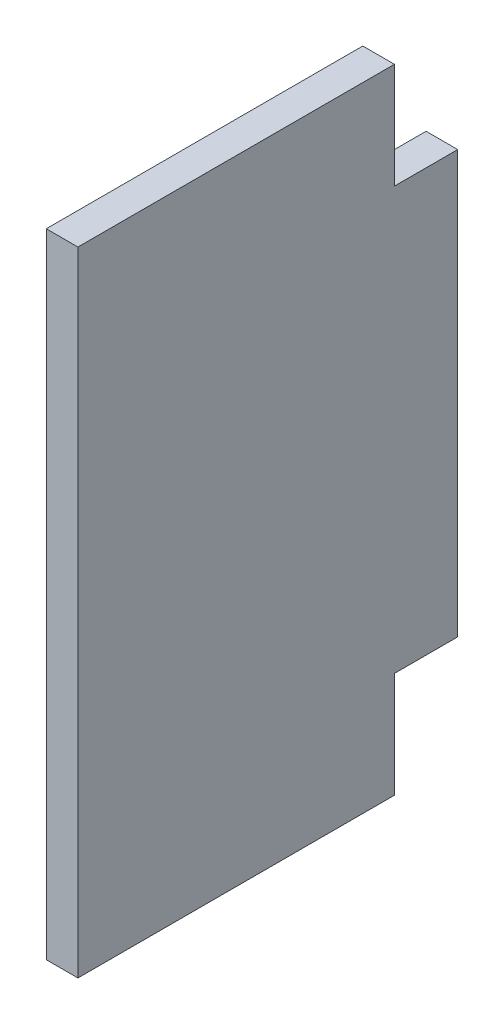
SolidWorks part; units mm, degrees
material "PVC rigido"
ref_plane "Piano frontale" through (0, 0, 0) normal (0, 0, 1) x (1, 0, 0)
ref_plane "Piano superiore" through (0, 0, 0) normal (0, 1, 0) x (1, 0, 0)
ref_plane "Piano destro" through (0, 0, 0) normal (1, 0, 0) x (0, 0, -1)
sketch "Schizzo1" plane through (0, 0, 1) normal (0, 0, 1) x (1, 0, 0)
  line L1 (72.5423, 20) -> (69.5423, 20)
  line L2 (72.5423, 20) -> (72.5423, -20)
  line L3 (72.5423, -20) -> (69.5423, -20)
  line L4 (69.5423, 20) -> (69.5423, -20)
extrude "Estrusione-Estrusione1" add sketch "Schizzo1" along normal blind 30 and the other way up to surface (6 mm away)
ref_plane "Piano1" through (0, 0, 0) normal (0, 1, 0) x (1, 0, 0)
sketch "Schizzo2" plane through (0, 20, 0) normal (0, 1, 0) x (1, 0, 0)
  line L1 (69.5423, -1) -> (72.5423, -1)
  line L2 (69.5423, -1) -> (69.5423, -31)
  line L3 (69.5423, -31) -> (72.5423, -31)
  line L4 (72.5423, -1) -> (72.5423, -31)
extrude "Estrusione-Estrusione2" add sketch "Schizzo2" along normal blind 10
mirror "Specchia1" about plane through (0, 0, 0) normal (0, 1, 0) of "Estrusione-Estrusione2"
